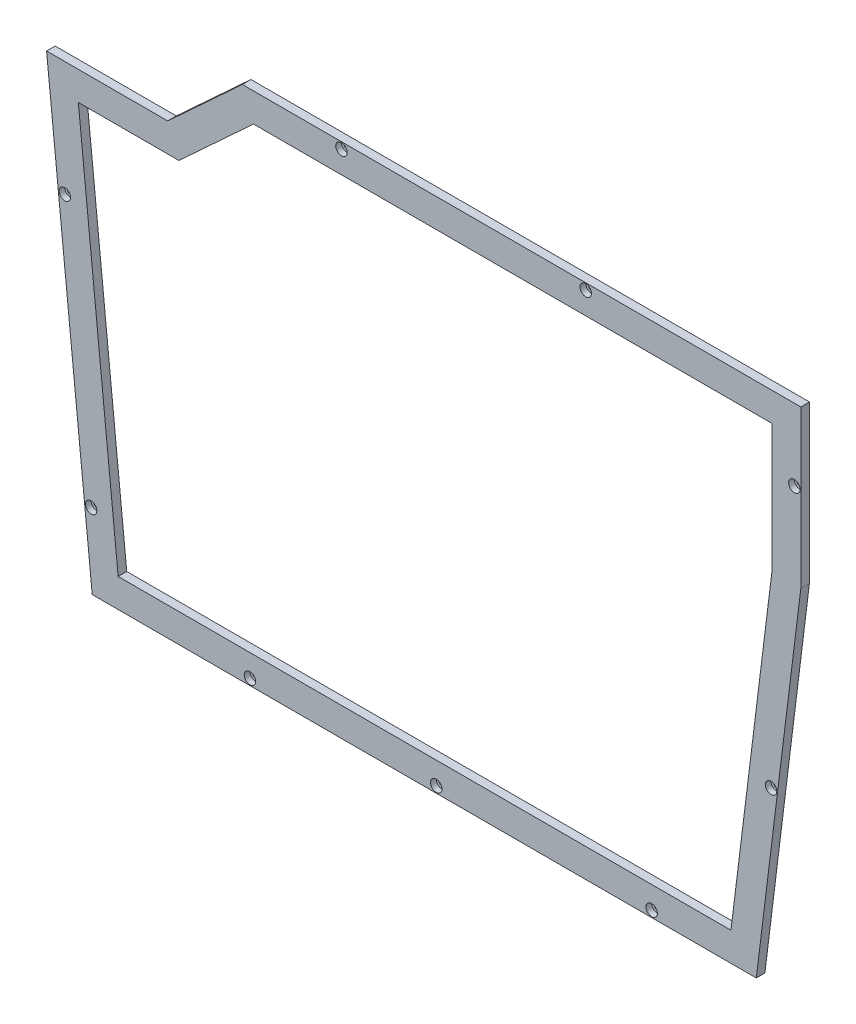
SolidWorks part; units mm, degrees
ref_plane "Plan de face" through (0, 0, 0) normal (0, 0, 1) x (1, 0, 0)
ref_plane "Plan de dessus" through (0, 0, 0) normal (0, 1, 0) x (1, 0, 0)
ref_plane "Plan de droite" through (0, 0, 0) normal (1, 0, 0) x (0, 0, -1)
sketch "Esquisse2" plane through (0, 0, 0) normal (0, 0, 1) x (1, 0, 0)
  line L0 (-10.9641, -65) -> (20.8708, -377.3)
  line L1 (20.8708, -377.3) -> (483.7977, -377.3)
  line L2 (483.7977, -377.3) -> (514.8433, -126.555)
  line L3 (514.8433, -126.555) -> (514.8433, -17)
  line L4 (514.8433, -17) -> (125.4811, -17)
  line L5 (125.4811, -17) -> (73.4811, -65)
  line L6 (73.4811, -65) -> (-10.9641, -65)
  line L7 (77.391, -75) -> (0.1071, -75)
  line L8 (0.1071, -75) -> (29.9032, -367.3)
  line L9 (29.9032, -367.3) -> (474.9594, -367.3)
  line L10 (474.9594, -367.3) -> (504.8433, -125.9383)
  line L11 (504.8433, -125.9383) -> (504.8433, -27)
  line L12 (504.8433, -27) -> (129.391, -27)
  line L13 (129.391, -27) -> (77.391, -75)
  line L14 (77.391, -75) -> (0.1071, -75) construction
  line L15 (0.1071, -75) -> (29.9032, -367.3) construction
  line L16 (29.9032, -367.3) -> (474.9594, -367.3) construction
  line L17 (474.9594, -367.3) -> (504.8433, -125.9383) construction
  line L18 (504.8433, -125.9383) -> (504.8433, -27) construction
  line L19 (504.8433, -27) -> (129.391, -27) construction
  line L20 (129.391, -27) -> (77.391, -75) construction
  line L21 (11.1783, -85) -> (38.9357, -357.3)
  line L22 (38.9357, -357.3) -> (466.1212, -357.3)
  line L23 (466.1212, -357.3) -> (494.8433, -125.3216)
  line L24 (494.8433, -125.3216) -> (494.8433, -37)
  line L25 (494.8433, -37) -> (133.3008, -37)
  line L26 (133.3008, -37) -> (81.3008, -85)
  line L27 (81.3008, -85) -> (11.1783, -85)
  dimension "D1" = 0
  dimension "D2" = 10
  dimension "D3" = 10
extrude "Boss.-Extru.1" add sketch "Esquisse2" along normal blind 6
hole_wizard "Chambrage pour vis à tête cylindrique à 6 pans creux (ou vis CHC) M41" positions "Esquisse5" profile "Esquisse4" counterbore size "M4" standard "Ansi Metric"
sketch "Esquisse5" plane through (0, 0, 6) normal (0, 0, 1) x (1, 0, 0)
  line L42 (479.8205, -372.8) -> (510.3433, -126.2775)
  line L43 (510.3433, -126.2775) -> (510.3433, -21.5)
  line L44 (510.3433, -21.5) -> (127.2406, -21.5)
  line L45 (127.2406, -21.5) -> (75.2406, -69.5)
  line L46 (75.2406, -69.5) -> (-5.982, -69.5)
  line L47 (24.9354, -372.8) -> (479.8205, -372.8)
  line L48 (-5.982, -69.5) -> (24.9354, -372.8)
  line L49 (479.8205, -372.8) -> (510.3433, -126.2775) construction
  line L50 (510.3433, -126.2775) -> (510.3433, -21.5) construction
  line L51 (510.3433, -21.5) -> (127.2406, -21.5) construction
  line L52 (127.2406, -21.5) -> (75.2406, -69.5) construction
  line L53 (75.2406, -69.5) -> (-5.982, -69.5) construction
  line L54 (24.9354, -372.8) -> (479.8205, -372.8) construction
  line L55 (-5.982, -69.5) -> (24.9354, -372.8) construction
  point P0 (1.7267, -145.1226)
  point P2 (20.068, -325.0511)
  point P4 (130.8195, -372.8)
  point P6 (260.6959, -372.8)
  point P8 (410.8708, -372.8)
  point P11 (494.1096, -257.3915)
  point P13 (510.3433, -67.0321)
  point P15 (364.9123, -21.5)
  point P17 (194.6066, -21.5)
  dimension "D1" = 4.5
sketch "Esquisse4" plane through (1.7267, -145.1226, 6) normal (1, 0, 0) x (0, -1, 0)
  line L0 (0, 0) -> (0, 15.2919)
  line L1 (0, 15.2919) -> (2.15, 14)
  line L2 (2.15, 14) -> (2.15, 4)
  line L3 (2.15, 4) -> (4, 4)
  line L4 (4, 4) -> (4, 0)
  line L5 (4, 0) -> (0, 0)
  line L10 (0, 15.2919) -> (-2.15, 14) construction
  line L11 (0, -6.35) -> (0, 107.95) construction
  dimension "Diamètre du perçage" = 4.3
  dimension "Profondeur du perçage" = 14
  dimension "Diamètre du chambrage" = 8
  dimension "Profondeur du chambrage" = 4
  dimension "Angle de pointe" = 118
